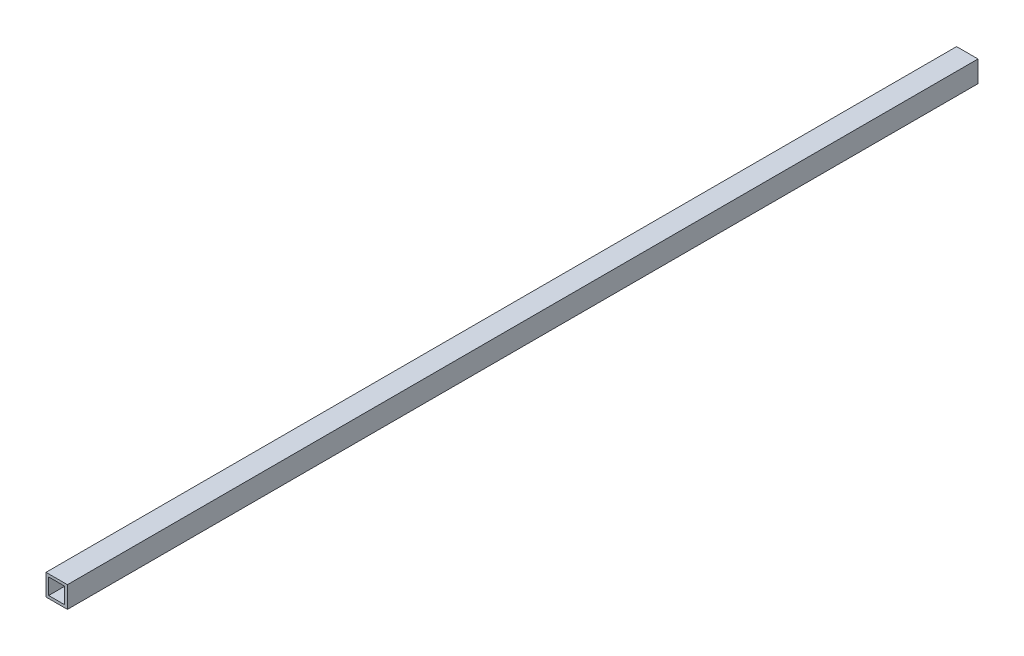
SolidWorks part; units mm, degrees
ref_plane "前视基准面" through (0, 0, 0) normal (0, 0, 1) x (1, 0, 0)
ref_plane "上视基准面" through (0, 0, 0) normal (0, 1, 0) x (1, 0, 0)
ref_plane "右视基准面" through (0, 0, 0) normal (1, 0, 0) x (0, 0, -1)
sketch "草图1" plane through (0, 0, 0) normal (0, 0, 1) x (1, 0, 0)
  line L1 (20, -20) -> (-20, -20)
  line L2 (20, -20) -> (20, 20)
  line L3 (20, 20) -> (-20, 20)
  line L4 (-20, -20) -> (-20, 20)
  line L5 (20, -20) -> (-20, 20) construction
  line L6 (20, 20) -> (-20, -20) construction
  point P0 (0, 0)
  dimension "D1" = 40
  dimension "D2" = 40
extrude "凸台-拉伸1" add sketch "草图1" along normal blind 1700
shell "抽壳1" thickness 5
